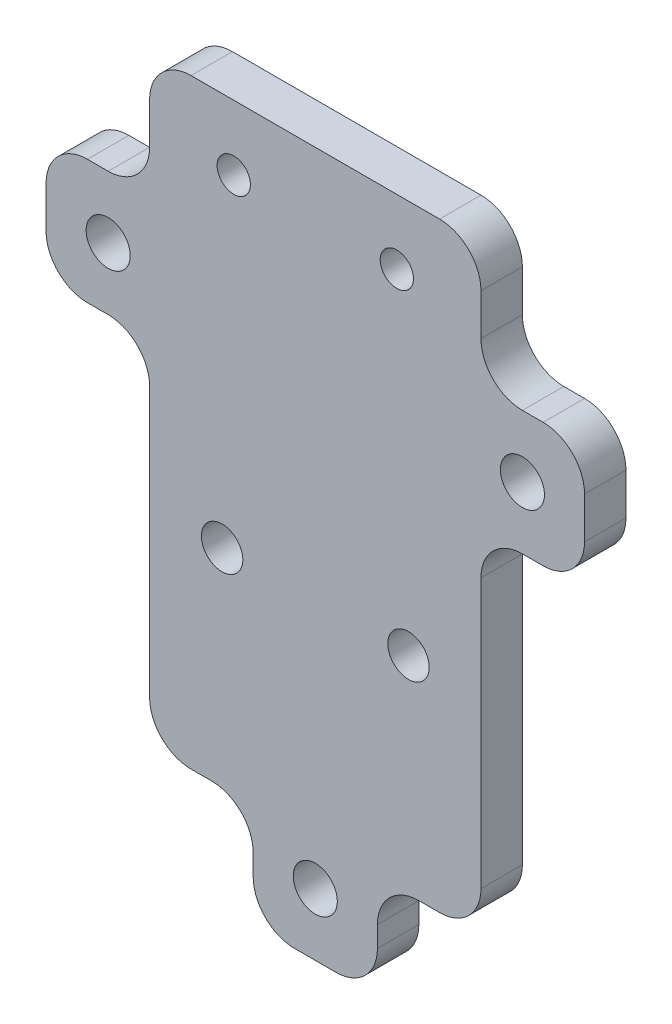
SolidWorks part; units mm, degrees
material "PC High Viscosity"
ref_plane "Front Plane" through (0, 0, 0) normal (0, 0, 1) x (1, 0, 0)
ref_plane "Top Plane" through (0, 0, 0) normal (0, 1, 0) x (1, 0, 0)
ref_plane "Right Plane" through (0, 0, 0) normal (1, 0, 0) x (0, 0, -1)
sketch "Sketch1" plane through (0, 0, 0) normal (0, 0, 1) x (1, 0, 0)
  line L0 (25.4, 0) -> (25.4, 101.6) construction
  line L1 (0, 0) -> (50.8, 0)
  line L2 (0, 0) -> (0, 101.6)
  line L3 (0, 101.6) -> (50.8, 101.6)
  line L4 (50.8, 0) -> (50.8, 101.6)
  point P5 (12.9, 82.139)
  point P6 (37.9, 82.139)
  dimension "D1" = 25
  dimension "D2" = 19.461
  dimension "D3" = 50.8
  dimension "D4" = 101.6
extrude "Boss-Extrude1" add sketch "Sketch1" along normal blind 6.35
hole_wizard "#7 (0.201) Diameter Hole1" positions "Sketch2" profile "Sketch3" hole size "#7" standard "ANSI Inch" end condition through all
sketch "Sketch2" plane through (0, 0, 6.35) normal (0, 0, 1) x (1, 0, 0)
  point P0 (12.9, 82.139)
  point P3 (37.9, 82.139)
sketch "Sketch3" plane through (12.9, 82.139, 6.35) normal (1, 0, 0) x (0, -1, 0)
  line L0 (0, 0) -> (0, 6.35)
  line L1 (0, 6.35) -> (2.5527, 6.35)
  line L2 (2.5527, 6.35) -> (2.5527, 0)
  line L5 (2.5527, 0) -> (0, 0)
  line L11 (0, -6.35) -> (0, 107.95) construction
  dimension "Thru Hole Dia." = 5.1054
  dimension "Thru Hole Depth" = 6.35
sketch "Sketch4" plane through (0, 0, 6.35) normal (0, 0, 1) x (1, 0, 0)
  line L0 (0, 101.6) -> (0, 0) construction
  line L1 (0, 73.025) -> (-15.875, 73.025)
  line L2 (0, 73.025) -> (0, 53.975)
  line L3 (0, 53.975) -> (-15.875, 53.975)
  line L4 (-15.875, 73.025) -> (-15.875, 53.975)
  line L5 (25.4, 0) -> (25.4, 101.6) construction
  line L6 (0, 0) -> (50.8, 0) construction
  line L7 (50.8, 101.6) -> (0, 101.6) construction
  line L8 (66.675, 73.025) -> (66.675, 53.975)
  line L9 (50.8, 53.975) -> (66.675, 53.975)
  line L10 (50.8, 73.025) -> (50.8, 53.975)
  line L11 (50.8, 73.025) -> (66.675, 73.025)
  line L13 (15.875, 0) -> (34.925, 0)
  line L14 (15.875, 0) -> (15.875, -15.875)
  line L15 (15.875, -15.875) -> (34.925, -15.875)
  line L16 (34.925, 0) -> (34.925, -15.875)
  point P12 (0, 63.5)
  point P13 (50.8, 63.5)
  dimension "D1" = 63.5
  dimension "D2" = 15.875
  dimension "D3" = 19.05
extrude "Boss-Extrude2" add sketch "Sketch4" against normal up to surface (6.35 mm away) up to face at (15.4527, 82.139, 0)
hole_wizard "1/4 Clearance Hole1" positions "Sketch5" profile "Sketch6" hole size "1/4" standard "ANSI Inch" end condition through all
sketch "Sketch5" plane through (0, 0, 6.35) normal (0, 0, 1) x (1, 0, 0)
  line L0 (-15.875, 63.5) -> (66.675, 63.5) construction
  line L1 (-15.875, 73.025) -> (-15.875, 53.975) construction
  line L2 (66.675, 53.975) -> (66.675, 73.025) construction
  line L3 (25.4, -15.875) -> (25.4, 101.6) construction
  line L4 (15.875, -15.875) -> (34.925, -15.875) construction
  line L5 (50.8, 101.6) -> (0, 101.6) construction
  point P0 (-6.35, 63.5)
  point P2 (57.15, 63.5)
  point P4 (25.4, -6.35)
  dimension "D1" = 9.525
  dimension "D2" = 9.525
  dimension "D3" = 63.5
  dimension "D4" = 69.85
sketch "Sketch6" plane through (-6.35, 63.5, 6.35) normal (1, 0, 0) x (0, -1, 0)
  line L0 (0, 0) -> (0, 6.35)
  line L1 (0, 6.35) -> (3.3782, 6.35)
  line L2 (3.3782, 6.35) -> (3.3782, 0)
  line L5 (3.3782, 0) -> (0, 0)
  line L11 (0, -6.35) -> (0, 107.95) construction
  dimension "Thru Hole Dia." = 6.7564
  dimension "Thru Hole Depth" = 6.35
sketch "Sketch7" plane through (0, 0, 0) normal (0, 0, -1) x (-1, 0, 0)
  line L0 (0, 101.6) -> (0, 73.025) construction
  line L1 (-50.8, 101.6) -> (0, 101.6)
  line L2 (-50.8, 101.6) -> (-50.8, 92.075)
  line L3 (-50.8, 92.075) -> (0, 92.075)
  line L4 (0, 101.6) -> (0, 92.075)
  dimension "D1" = 9.525
extrude "Cut-Extrude1" cut sketch "Sketch7" against normal through all
fillet "Fillet1" radius 6.35 16 edges at (0, 73.025, 3.175) (-15.875, 73.025, 3.175) (0, 0, 3.175) (15.875, 0, 3.175) (15.875, -15.875, 3.175) (34.925, -15.875, 3.175) (34.925, 0, 3.175) (50.8, 0, 3.175) (50.8, 53.975, 3.175) (66.675, 53.975, 3.175) (66.675, 73.025, 3.175) (50.8, 73.025, 3.175) (0, 53.975, 3.175) (-15.875, 53.975, 3.175) (0, 92.075, 3.175) (50.8, 92.075, 3.175)
hole_wizard "1/4 (0.25) Diameter Hole1" positions "Sketch8" profile "Sketch9" hole size "1/4" standard "ANSI Inch" end condition through all
sketch "Sketch8" plane through (0, 0, 0) normal (0, 0, -1) x (-1, 0, 0)
  line L0 (-25.4, -15.875) -> (-25.4, 92.075) construction
  line L1 (-22.225, -15.875) -> (-28.575, -15.875) construction
  line L2 (-44.45, 92.075) -> (-6.35, 92.075) construction
  line L3 (-41.275, 0) -> (-44.45, 0) construction
  point P0 (-39.6875, 31.75)
  point P15 (-11.1125, 31.75)
  dimension "D1" = 28.575
  dimension "D2" = 31.75
sketch "Sketch9" plane through (39.6875, 31.75, 0) normal (1, 0, 0) x (0, 1, 0)
  line L0 (0, 0) -> (0, 6.35)
  line L1 (0, 6.35) -> (3.175, 6.35)
  line L2 (3.175, 6.35) -> (3.175, 0)
  line L5 (3.175, 0) -> (0, 0)
  line L11 (0, -6.35) -> (0, 107.95) construction
  dimension "Thru Hole Dia." = 6.35
  dimension "Thru Hole Depth" = 6.35
equation "\"D1@Sketch1\"=25mm"
equation "\"D2@Sketch1\"=14mm+.2in+.015"
